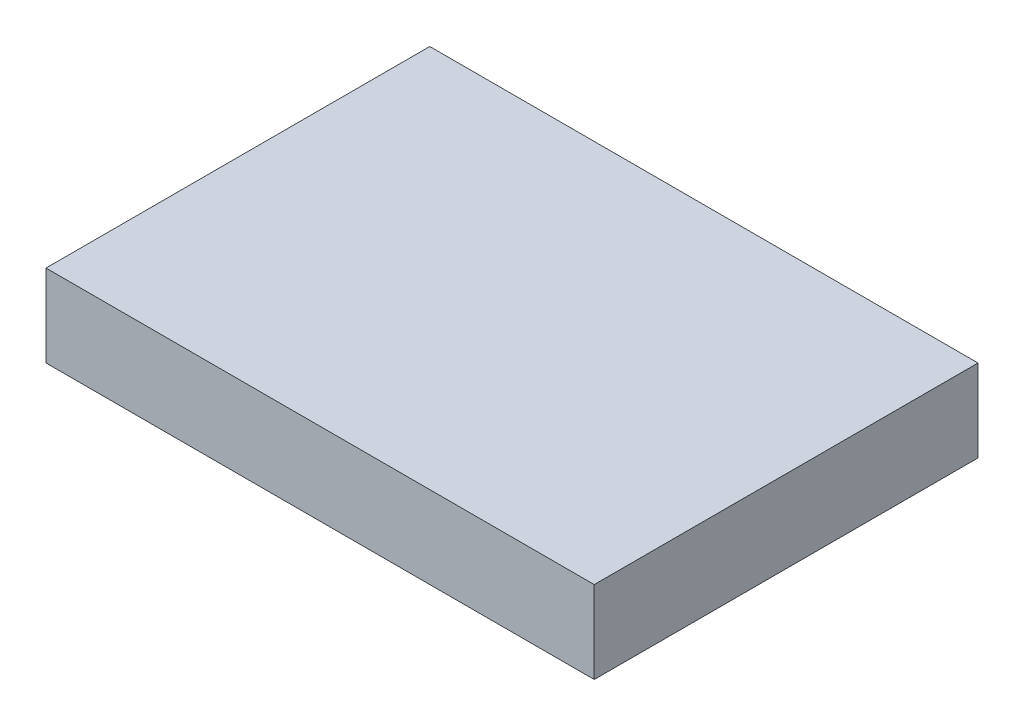
SolidWorks part; units mm, degrees
ref_plane "Front Plane" through (0, 0, 0) normal (0, 0, 1) x (1, 0, 0)
ref_plane "Top Plane" through (0, 0, 0) normal (0, 1, 0) x (1, 0, 0)
ref_plane "Right Plane" through (0, 0, 0) normal (1, 0, 0) x (0, 0, -1)
sketch "Sketch1" plane through (0, 0, 0) normal (0, 1, 0) x (1, 0, 0)
  line L1 (-50, -35) -> (50, -35)
  line L2 (-50, -35) -> (-50, 35)
  line L3 (-50, 35) -> (50, 35)
  line L4 (50, -35) -> (50, 35)
  line L5 (-50, -35) -> (50, 35) construction
  line L6 (-50, 35) -> (50, -35) construction
  point P0 (0, 0)
  dimension "D1" = 70
  dimension "D2" = 100
extrude "Boss-Extrude1" add sketch "Sketch1" along normal blind 15
